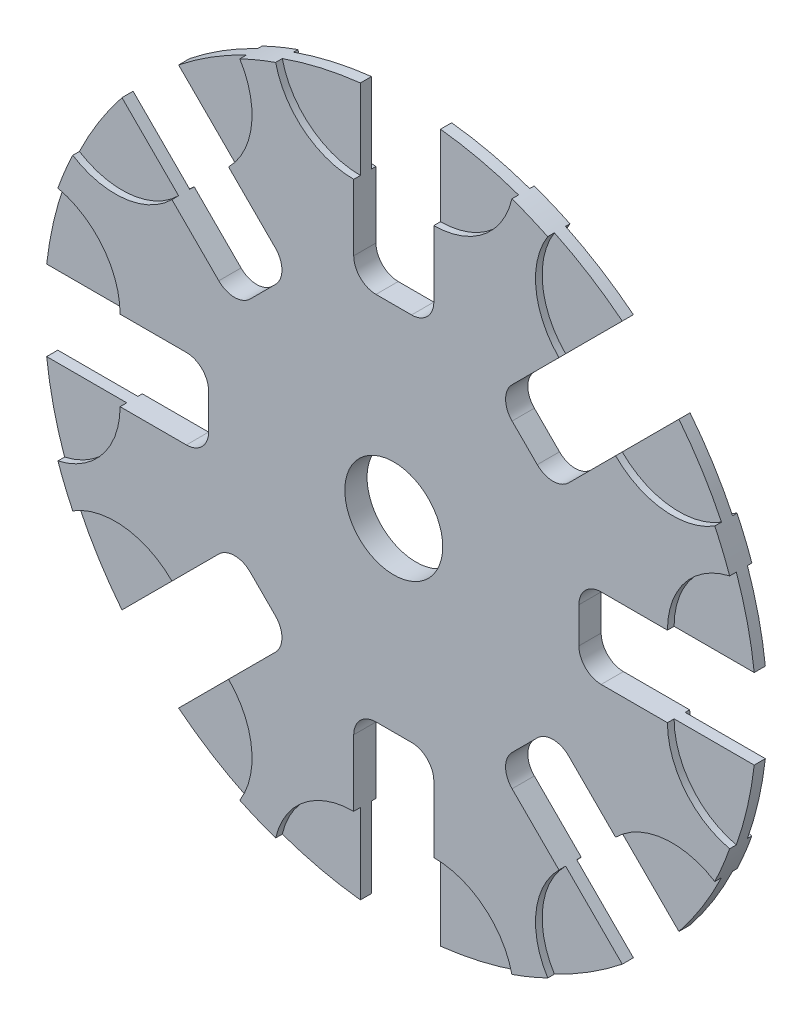
SolidWorks part; units mm, degrees
ref_plane "Front Plane" through (0, 0, 0) normal (0, 0, 1) x (1, 0, 0)
ref_plane "Top Plane" through (0, 0, 0) normal (0, 1, 0) x (1, 0, 0)
ref_plane "Right Plane" through (0, 0, 0) normal (1, 0, 0) x (0, 0, -1)
sketch "Sketch1" plane through (0, 0, 0) normal (0, 0, 1) x (1, 0, 0)
  line L0 (0, 80) -> (0, -80) construction
  line L1 (-80, 0) -> (80, 0) construction
  line L2 (9, -46.6) -> (9, -79.4921)
  line L3 (-4, 41.6) -> (4, 41.6)
  line L4 (-9, 46.6) -> (-9, 79.4921)
  line L6 (9, 46.6) -> (9, 79.4921)
  line L7 (-4, -41.6) -> (4, -41.6)
  line L8 (-9, -46.6) -> (-9, -79.4921)
  line L9 (41.6, 4) -> (41.6, -4)
  line L10 (46.6, -9) -> (79.4921, -9)
  line L11 (46.6, 9) -> (79.4921, 9)
  line L12 (-46.6, -9) -> (-79.4921, -9)
  line L13 (-41.6, 4) -> (-41.6, -4)
  line L14 (-46.6, 9) -> (-79.4921, 9)
  line L15 (26.5872, 32.2441) -> (32.2441, 26.5872)
  line L16 (39.3151, 26.5872) -> (62.5734, 49.8455)
  line L17 (26.5872, 39.3151) -> (49.8455, 62.5734)
  line L18 (-26.5872, 39.3151) -> (-49.8455, 62.5734)
  line L19 (-26.5872, 32.2441) -> (-32.2441, 26.5872)
  line L20 (-39.3151, 26.5872) -> (-62.5734, 49.8455)
  line L21 (0, 0) -> (56.5685, 56.5685) construction
  line L22 (0, 0) -> (-56.5685, 56.5685) construction
  line L23 (-26.5872, -39.3151) -> (-49.8455, -62.5734)
  line L24 (-26.5872, -32.2441) -> (-32.2441, -26.5872)
  line L25 (-39.3151, -26.5872) -> (-62.5734, -49.8455)
  line L26 (26.5872, -39.3151) -> (49.8455, -62.5734)
  line L27 (26.5872, -32.2441) -> (32.2441, -26.5872)
  line L28 (39.3151, -26.5872) -> (62.5734, -49.8455)
  circle A0 centre (0, 0) radius 80
  arc A1 (41.6, 4) -> (46.6, 9) centre (46.6, 4) cw
  arc A2 (41.6, -4) -> (46.6, -9) centre (46.6, -4) ccw
  arc A3 (32.2441, -26.5872) -> (39.3151, -26.5872) centre (35.7796, -30.1227) cw
  arc A4 (26.5872, -32.2441) -> (26.5872, -39.3151) centre (30.1227, -35.7796) ccw
  arc A5 (4, -41.6) -> (9, -46.6) centre (4, -46.6) cw
  arc A6 (-4, -41.6) -> (-9, -46.6) centre (-4, -46.6) ccw
  arc A7 (-26.5872, -32.2441) -> (-26.5872, -39.3151) centre (-30.1227, -35.7796) cw
  arc A8 (-32.2441, -26.5872) -> (-39.3151, -26.5872) centre (-35.7796, -30.1227) ccw
  arc A9 (-46.6, -9) -> (-41.6, -4) centre (-46.6, -4) ccw
  arc A10 (-41.6, 4) -> (-46.6, 9) centre (-46.6, 4) ccw
  arc A11 (-26.5872, 39.3151) -> (-26.5872, 32.2441) centre (-30.1227, 35.7796) cw
  arc A12 (-32.2441, 26.5872) -> (-39.3151, 26.5872) centre (-35.7796, 30.1227) cw
  arc A13 (-4, 41.6) -> (-9, 46.6) centre (-4, 46.6) cw
  arc A14 (4, 41.6) -> (9, 46.6) centre (4, 46.6) ccw
  arc A15 (32.2441, 26.5872) -> (39.3151, 26.5872) centre (35.7796, 30.1227) ccw
  arc A16 (26.5872, 32.2441) -> (26.5872, 39.3151) centre (30.1227, 35.7796) cw
  arc A17 (34.5941, 72.1335) -> (37.1175, 49.8455) centre (49.8455, 62.5734) ccw
  arc A18 (49.8455, 37.1175) -> (72.1335, 34.5941) centre (62.5734, 49.8455) ccw
  arc A19 (-34.5941, 72.1335) -> (-37.1175, 49.8455) centre (-49.8455, 62.5734) cw
  arc A20 (-49.8455, 37.1175) -> (-72.1335, 34.5941) centre (-62.5734, 49.8455) cw
  arc A21 (-49.8455, -37.1175) -> (-72.1335, -34.5941) centre (-62.5734, -49.8455) ccw
  arc A22 (-34.5941, -72.1335) -> (-37.1175, -49.8455) centre (-49.8455, -62.5734) ccw
  arc A23 (34.5941, -72.1335) -> (37.1175, -49.8455) centre (49.8455, -62.5734) cw
  arc A24 (49.8455, -37.1175) -> (72.1335, -34.5941) centre (62.5734, -49.8455) cw
  arc A25 (-26.5444, 75.4678) -> (-9, 61.4921) centre (-9, 79.4921) ccw
  arc A26 (9, 61.4921) -> (26.5444, 75.4678) centre (9, 79.4921) ccw
  arc A27 (-26.5444, -75.4678) -> (-9, -61.4921) centre (-9, -79.4921) cw
  arc A28 (9, -61.4921) -> (26.5444, -75.4678) centre (9, -79.4921) cw
  arc A29 (-61.4921, 9) -> (-75.4678, 26.5444) centre (-79.4921, 9) ccw
  arc A30 (-75.4678, -26.5444) -> (-61.4921, -9) centre (-79.4921, -9) ccw
  arc A31 (61.4921, 9) -> (75.4678, 26.5444) centre (79.4921, 9) cw
  arc A32 (75.4678, -26.5444) -> (61.4921, -9) centre (79.4921, -9) cw
  circle A33 centre (0, 0) radius 11
  point P44 (41.6, 9)
  point P47 (41.6, -9)
  point P50 (35.7796, -23.0517)
  point P53 (23.0517, -35.7796)
  point P56 (9, -41.6)
  point P59 (-9, -41.6)
  point P62 (-23.0517, -35.7796)
  point P65 (-35.7796, -23.0517)
  point P68 (-41.6, -9)
  point P71 (-41.6, 9)
  point P74 (-23.0517, 35.7796)
  point P77 (-35.7796, 23.0517)
  point P80 (-9, 41.6)
  point P83 (9, 41.6)
  point P86 (35.7796, 23.0517)
  point P89 (23.0517, 35.7796)
  dimension "D1" = 160
  dimension "D13" = 5
  dimension "D14" = 18
  dimension "D15" = 18
  dimension "D16" = 18
  dimension "D17" = 18
  dimension "D18" = 18
  dimension "D20" = 22
  dimension "D2" = 41.6
  dimension "D3" = 41.6
  dimension "D4" = 41.6
  dimension "D5" = 9
  dimension "D6" = 9
  dimension "D7" = 9
  dimension "D8" = 45
  dimension "D9" = 45
  dimension "D10" = 9
  dimension "D11" = 9
  dimension "D12" = 9
  dimension "D19" = 18
extrude "Boss-Extrude1" add sketch "Sketch1" along normal blind 5 contours A0 A32 L10 A2 L9 A1 L11 A31 A18 L16 A15 L15 A16 L17 A17 A26 L6 A14 L3 A13 L4 A25 A19 L18 A11 L19 A12 L20 A20 A29 L14 A10 L13 A9 L12 A30 A21 L25 A8 L24 A7 L23 A22 A27 L8
sketch "Sketch2" plane through (0, 0, 5) normal (0, 0, 1) x (1, 0, 0)
  line L0 (46.6, -9) -> (79.4921, -9) construction
  line L1 (41.6, 4) -> (41.6, -4) construction
  line L2 (46.6, 9) -> (79.4921, 9) construction
  line L3 (9, -46.6) -> (9, -79.4921) construction
  line L4 (-4, -41.6) -> (4, -41.6) construction
  line L5 (-9, -46.6) -> (-9, -79.4921) construction
  line L6 (-9, 46.6) -> (-9, 79.4921) construction
  line L7 (-4, 41.6) -> (4, 41.6) construction
  line L8 (9, 46.6) -> (9, 79.4921) construction
  line L9 (-26.5872, 39.3151) -> (-49.8455, 62.5734) construction
  line L10 (-26.5872, 32.2441) -> (-32.2441, 26.5872) construction
  line L11 (-39.3151, 26.5872) -> (-62.5734, 49.8455) construction
  line L12 (39.3151, 26.5872) -> (62.5734, 49.8455) construction
  line L13 (26.5872, 32.2441) -> (32.2441, 26.5872) construction
  line L14 (26.5872, 39.3151) -> (49.8455, 62.5734) construction
  line L15 (-46.6, -9) -> (-79.4921, -9) construction
  line L16 (-41.6, 4) -> (-41.6, -4) construction
  line L17 (-46.6, 9) -> (-79.4921, 9) construction
  line L18 (26.5872, -39.3151) -> (49.8455, -62.5734) construction
  line L19 (26.5872, -32.2441) -> (32.2441, -26.5872) construction
  line L20 (39.3151, -26.5872) -> (62.5734, -49.8455) construction
  line L21 (-39.3151, -26.5872) -> (-62.5734, -49.8455) construction
  line L22 (-26.5872, -32.2441) -> (-32.2441, -26.5872) construction
  line L23 (-26.5872, -39.3151) -> (-49.8455, -62.5734) construction
  line L24 (46.6, -9) -> (79.4921, -9)
  line L25 (41.6, 4) -> (41.6, -4)
  line L26 (46.6, 9) -> (79.4921, 9)
  line L27 (9, -46.6) -> (9, -79.4921)
  line L28 (-4, -41.6) -> (4, -41.6)
  line L29 (-9, -46.6) -> (-9, -79.4921)
  line L30 (-9, 46.6) -> (-9, 79.4921)
  line L31 (-4, 41.6) -> (4, 41.6)
  line L32 (9, 46.6) -> (9, 79.4921)
  line L33 (-26.5872, 39.3151) -> (-49.8455, 62.5734)
  line L34 (-26.5872, 32.2441) -> (-32.2441, 26.5872)
  line L35 (-39.3151, 26.5872) -> (-62.5734, 49.8455)
  line L36 (39.3151, 26.5872) -> (62.5734, 49.8455)
  line L37 (26.5872, 32.2441) -> (32.2441, 26.5872)
  line L38 (26.5872, 39.3151) -> (49.8455, 62.5734)
  line L39 (-46.6, -9) -> (-79.4921, -9)
  line L40 (-41.6, 4) -> (-41.6, -4)
  line L41 (-46.6, 9) -> (-79.4921, 9)
  line L42 (26.5872, -39.3151) -> (49.8455, -62.5734)
  line L43 (26.5872, -32.2441) -> (32.2441, -26.5872)
  line L44 (39.3151, -26.5872) -> (62.5734, -49.8455)
  line L45 (-39.3151, -26.5872) -> (-62.5734, -49.8455)
  line L46 (-26.5872, -32.2441) -> (-32.2441, -26.5872)
  line L47 (-26.5872, -39.3151) -> (-49.8455, -62.5734)
  arc A0 (41.6, -4) -> (46.6, -9) centre (46.6, -4) ccw construction
  circle A1 centre (0, 0) radius 80
  circle A2 centre (0, 0) radius 80
  circle A3 centre (0, 0) radius 11
  circle A4 centre (0, 0) radius 11
  arc A5 (46.6, 9) -> (41.6, 4) centre (46.6, 4) ccw construction
  arc A6 (9, -46.6) -> (4, -41.6) centre (4, -46.6) ccw construction
  arc A7 (-4, -41.6) -> (-9, -46.6) centre (-4, -46.6) ccw construction
  arc A8 (-9, 46.6) -> (-4, 41.6) centre (-4, 46.6) ccw construction
  arc A9 (4, 41.6) -> (9, 46.6) centre (4, 46.6) ccw construction
  arc A10 (34.5941, 72.1335) -> (37.1175, 49.8455) centre (49.8455, 62.5734) ccw construction
  arc A11 (-26.5872, 32.2441) -> (-26.5872, 39.3151) centre (-30.1227, 35.7796) ccw construction
  arc A12 (-39.3151, 26.5872) -> (-32.2441, 26.5872) centre (-35.7796, 30.1227) ccw construction
  arc A13 (32.2441, 26.5872) -> (39.3151, 26.5872) centre (35.7796, 30.1227) ccw construction
  arc A14 (26.5872, 39.3151) -> (26.5872, 32.2441) centre (30.1227, 35.7796) ccw construction
  arc A15 (-46.6, -9) -> (-41.6, -4) centre (-46.6, -4) ccw construction
  arc A16 (-41.6, 4) -> (-46.6, 9) centre (-46.6, 4) ccw construction
  arc A17 (26.5872, -32.2441) -> (26.5872, -39.3151) centre (30.1227, -35.7796) ccw construction
  arc A18 (39.3151, -26.5872) -> (32.2441, -26.5872) centre (35.7796, -30.1227) ccw construction
  arc A19 (-32.2441, -26.5872) -> (-39.3151, -26.5872) centre (-35.7796, -30.1227) ccw construction
  arc A20 (-26.5872, -39.3151) -> (-26.5872, -32.2441) centre (-30.1227, -35.7796) ccw construction
  arc A21 (-72.1335, 34.5941) -> (-49.8455, 37.1175) centre (-62.5734, 49.8455) ccw construction
  arc A22 (-37.1175, 49.8455) -> (-34.5941, 72.1335) centre (-49.8455, 62.5734) ccw construction
  arc A23 (49.8455, 37.1175) -> (72.1335, 34.5941) centre (62.5734, 49.8455) ccw construction
  arc A24 (26.5444, -75.4678) -> (9, -61.4921) centre (9, -79.4921) ccw construction
  arc A25 (-9, -61.4921) -> (-26.5444, -75.4678) centre (-9, -79.4921) ccw construction
  arc A26 (9, 61.4921) -> (26.5444, 75.4678) centre (9, 79.4921) ccw construction
  arc A27 (-26.5444, 75.4678) -> (-9, 61.4921) centre (-9, 79.4921) ccw construction
  arc A28 (72.1335, -34.5941) -> (49.8455, -37.1175) centre (62.5734, -49.8455) ccw construction
  arc A29 (37.1175, -49.8455) -> (34.5941, -72.1335) centre (49.8455, -62.5734) ccw construction
  arc A30 (-34.5941, -72.1335) -> (-37.1175, -49.8455) centre (-49.8455, -62.5734) ccw construction
  arc A31 (-49.8455, -37.1175) -> (-72.1335, -34.5941) centre (-62.5734, -49.8455) ccw construction
  arc A32 (61.4921, -9) -> (75.4678, -26.5444) centre (79.4921, -9) ccw construction
  arc A33 (75.4678, 26.5444) -> (61.4921, 9) centre (79.4921, 9) ccw construction
  arc A34 (-75.4678, -26.5444) -> (-61.4921, -9) centre (-79.4921, -9) ccw construction
  arc A35 (-61.4921, 9) -> (-75.4678, 26.5444) centre (-79.4921, 9) ccw construction
  arc A36 (41.6, -4) -> (46.6, -9) centre (46.6, -4) ccw
  arc A37 (46.6, 9) -> (41.6, 4) centre (46.6, 4) ccw
  arc A38 (9, -46.6) -> (4, -41.6) centre (4, -46.6) ccw
  arc A39 (-4, -41.6) -> (-9, -46.6) centre (-4, -46.6) ccw
  arc A40 (-9, 46.6) -> (-4, 41.6) centre (-4, 46.6) ccw
  arc A41 (4, 41.6) -> (9, 46.6) centre (4, 46.6) ccw
  arc A42 (34.5941, 72.1335) -> (37.1175, 49.8455) centre (49.8455, 62.5734) ccw
  arc A43 (-26.5872, 32.2441) -> (-26.5872, 39.3151) centre (-30.1227, 35.7796) ccw
  arc A44 (-39.3151, 26.5872) -> (-32.2441, 26.5872) centre (-35.7796, 30.1227) ccw
  arc A45 (32.2441, 26.5872) -> (39.3151, 26.5872) centre (35.7796, 30.1227) ccw
  arc A46 (26.5872, 39.3151) -> (26.5872, 32.2441) centre (30.1227, 35.7796) ccw
  arc A47 (-46.6, -9) -> (-41.6, -4) centre (-46.6, -4) ccw
  arc A48 (-41.6, 4) -> (-46.6, 9) centre (-46.6, 4) ccw
  arc A49 (26.5872, -32.2441) -> (26.5872, -39.3151) centre (30.1227, -35.7796) ccw
  arc A50 (39.3151, -26.5872) -> (32.2441, -26.5872) centre (35.7796, -30.1227) ccw
  arc A51 (-32.2441, -26.5872) -> (-39.3151, -26.5872) centre (-35.7796, -30.1227) ccw
  arc A52 (-26.5872, -39.3151) -> (-26.5872, -32.2441) centre (-30.1227, -35.7796) ccw
  arc A53 (-72.1335, 34.5941) -> (-49.8455, 37.1175) centre (-62.5734, 49.8455) ccw
  arc A54 (-37.1175, 49.8455) -> (-34.5941, 72.1335) centre (-49.8455, 62.5734) ccw
  arc A55 (49.8455, 37.1175) -> (72.1335, 34.5941) centre (62.5734, 49.8455) ccw
  arc A56 (26.5444, -75.4678) -> (9, -61.4921) centre (9, -79.4921) ccw
  arc A57 (-9, -61.4921) -> (-26.5444, -75.4678) centre (-9, -79.4921) ccw
  arc A58 (9, 61.4921) -> (26.5444, 75.4678) centre (9, 79.4921) ccw
  arc A59 (-26.5444, 75.4678) -> (-9, 61.4921) centre (-9, 79.4921) ccw
  arc A60 (72.1335, -34.5941) -> (49.8455, -37.1175) centre (62.5734, -49.8455) ccw
  arc A61 (37.1175, -49.8455) -> (34.5941, -72.1335) centre (49.8455, -62.5734) ccw
  arc A62 (-34.5941, -72.1335) -> (-37.1175, -49.8455) centre (-49.8455, -62.5734) ccw
  arc A63 (-49.8455, -37.1175) -> (-72.1335, -34.5941) centre (-62.5734, -49.8455) ccw
  arc A64 (61.4921, -9) -> (75.4678, -26.5444) centre (79.4921, -9) ccw
  arc A65 (75.4678, 26.5444) -> (61.4921, 9) centre (79.4921, 9) ccw
  arc A66 (-75.4678, -26.5444) -> (-61.4921, -9) centre (-79.4921, -9) ccw
  arc A67 (-61.4921, 9) -> (-75.4678, 26.5444) centre (-79.4921, 9) ccw
  dimension "D1" = 0
  dimension "D2" = 0
extrude "Boss-Extrude2" add sketch "Sketch2" against normal blind 2.5 from offset 1.5 contours L33 A54 A2 | A2 A53 L35 | A2 A59 L30 | L32 A58 A2 | A2 A42 L38 | L36 A55 A2 | A2 A65 L26 | L24 A64 A2 | A2 A60 L44 | L42 A61 A2 | A2 A56 L27 | L29 A57 A2 | A2 A62 L47 | L45 A63 A2 | A2 A66 L39 | L41 A67 A2
